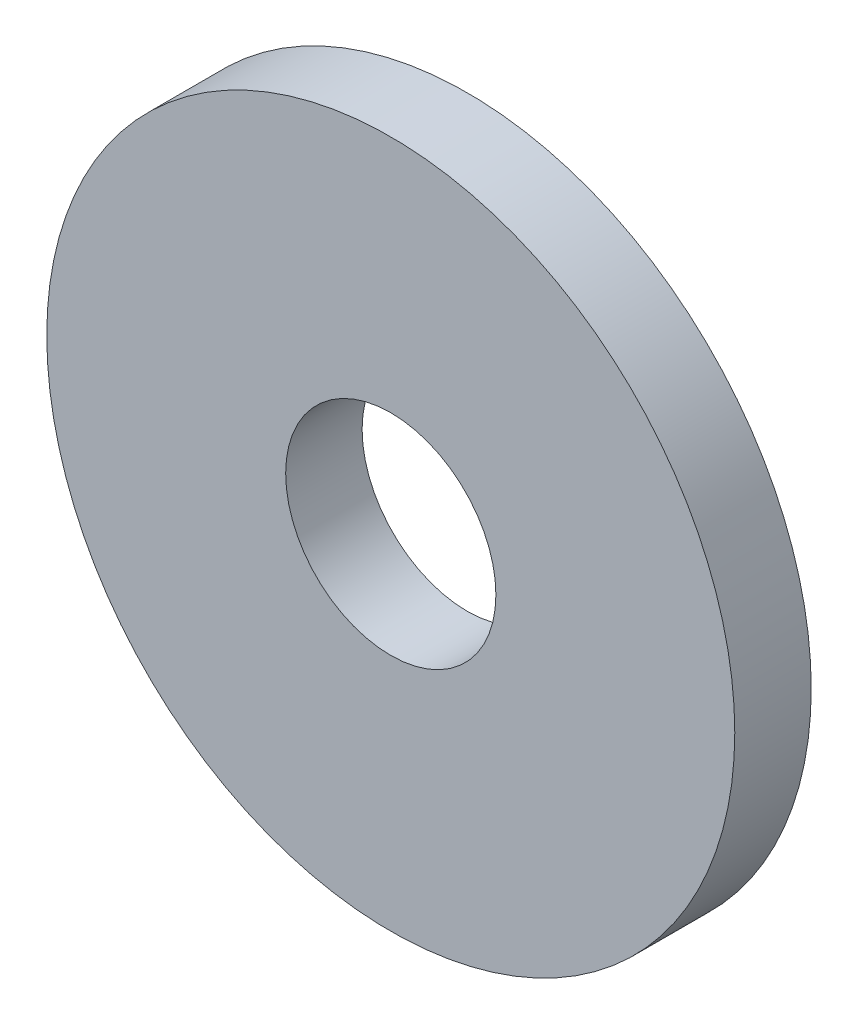
SolidWorks part; units mm, degrees
material "Acrylic (Medium-high impact)"
ref_plane "Front Plane" through (0, 0, 0) normal (0, 0, 1) x (1, 0, 0)
ref_plane "Top Plane" through (0, 0, 0) normal (0, 1, 0) x (1, 0, 0)
ref_plane "Right Plane" through (0, 0, 0) normal (1, 0, 0) x (0, 0, -1)
sketch "Model" plane through (0, 0, 0) normal (0, 0, 1) x (1, 0, 0)
  circle A131 centre (1974.6956, 1141.2418) radius 9
  circle A132 centre (1974.6956, 1141.2418) radius 2.75
extrude "Boss-Extrude1" add sketch "Model" along normal blind 2
